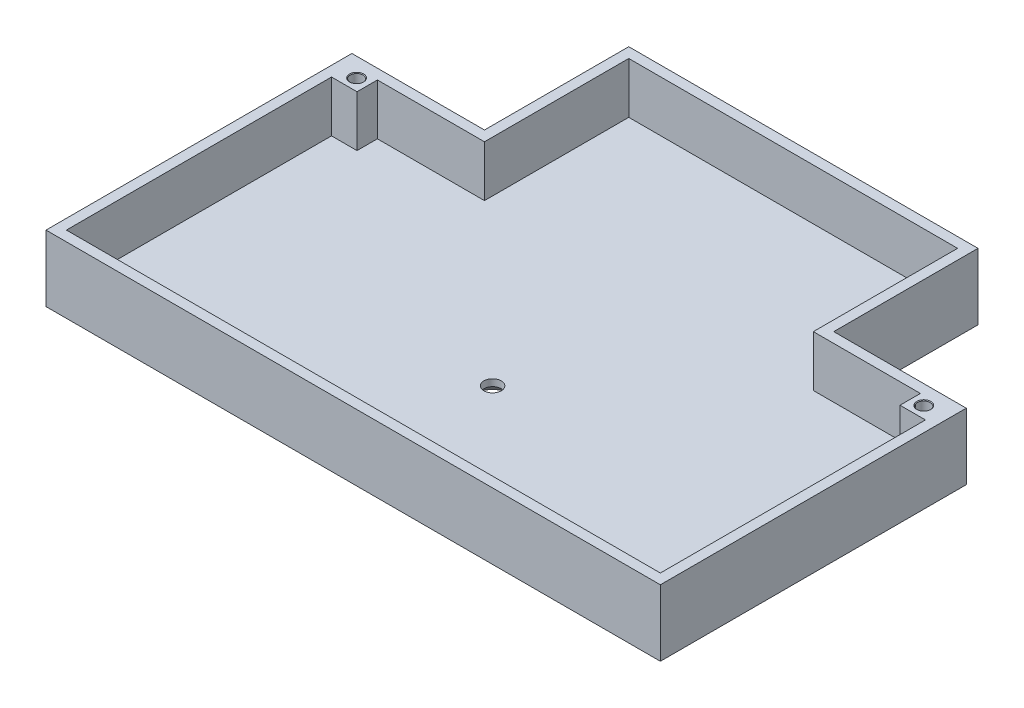
SolidWorks part; units mm, degrees
ref_plane "Front Plane" through (0, 0, 0) normal (0, 0, 1) x (1, 0, 0)
ref_plane "Top Plane" through (0, 0, 0) normal (0, 1, 0) x (1, 0, 0)
ref_plane "Right Plane" through (0, 0, 0) normal (1, 0, 0) x (0, 0, -1)
sketch "Sketch1" plane through (0, 0, 0) normal (0, 1, 0) x (1, 0, 0)
  line L1 (60.25, 30) -> (-60.25, 30)
  line L2 (60.25, 30) -> (60.25, -30)
  line L3 (60.25, -30) -> (-60.25, -30)
  line L4 (-60.25, 30) -> (-60.25, -30)
  line L5 (60.25, 30) -> (-60.25, -30) construction
  line L6 (60.25, -30) -> (-60.25, 30) construction
  point P0 (0, 0)
  dimension "D1" = 60
  dimension "D2" = 120.5
extrude "Boss-Extrude1" add sketch "Sketch1" along normal blind 3
sketch "Sketch3" plane through (0, 0, 0) normal (0, -1, 0) x (1, 0, 0)
  line L0 (-34.25, -30) -> (34.25, -30)
  line L1 (60.25, -30) -> (-60.25, -30) construction
  line L2 (34.25, -30) -> (34.25, -58.3)
  line L3 (34.25, -58.3) -> (-34.25, -58.3)
  line L4 (-34.25, -58.3) -> (-34.25, -30)
  line L5 (0, 0) -> (0, 17.3585) construction
  dimension "D1" = 26
  dimension "D2" = 28.3
extrude "Boss-Extrude3" add sketch "Sketch3" against normal blind 3
sketch "Sketch2" plane through (0, 3, 0) normal (0, 1, 0) x (1, 0, 0)
  line L0 (60.25, 30) -> (34.25, 30)
  line L2 (60.25, 30) -> (60.25, -30)
  line L3 (60.25, -30) -> (-60.25, -30)
  line L4 (-60.25, 30) -> (-60.25, -30)
  line L5 (34.25, 30) -> (34.25, 58.3)
  line L6 (34.25, 58.3) -> (-34.25, 58.3)
  line L11 (-34.25, 58.3) -> (-34.25, 30)
  line L12 (-34.25, 30) -> (-60.25, 30)
  line L13 (-32.25, 28) -> (-58.25, 28)
  line L14 (-58.25, 28) -> (-58.25, -28)
  line L15 (58.25, -28) -> (-58.25, -28)
  line L16 (58.25, 28) -> (58.25, -28)
  line L17 (58.25, 28) -> (32.25, 28)
  line L18 (32.25, 28) -> (32.25, 56.3)
  line L19 (32.25, 56.3) -> (-32.25, 56.3)
  line L20 (-32.25, 56.3) -> (-32.25, 28)
  point P0 (0, 0)
  point P7 (0, 0)
  dimension "D1" = 2
extrude "Boss-Extrude2" add sketch "Sketch2" along normal blind 10
hole_wizard "CSK for M3 Hex Socket Countersunk Cap Screw1" positions "Sketch4" profile "Sketch5" countersink size "M3" standard "ISO" end condition through all
sketch "Sketch4" plane through (0, 0, 0) normal (0, -1, 0) x (-1, 0, 0)
  line L0 (60.25, -30) -> (-60.25, -30) construction
  line L1 (0, 0) -> (0, 13.3485) construction
  point P0 (0, -2.66)
  dimension "D1" = 27.34
sketch "Sketch5" plane through (0, 0, 2.66) normal (1, 0, 0) x (0, 0, -1)
  line L0 (0, 0) -> (0, 13)
  line L1 (0, 13) -> (1.7, 13)
  line L2 (1.7, 13) -> (1.7, 1.66)
  line L3 (1.7, 1.66) -> (3.36, 0)
  line L5 (3.36, 0) -> (0, 0)
  line L6 (-1.7, 1.66) -> (-3.36, 0) construction
  line L11 (0, -6.35) -> (0, 107.95) construction
  dimension "Thru Hole Dia." = 3.4
  dimension "Thru Hole Depth" = 13
  dimension "Near C'Sink Dia." = 6.72
  dimension "Near C'Sink Angle" = 90
sketch "Sketch6" plane through (0, 3, 0) normal (0, 1, 0) x (1, 0, 0)
  line L1 (-58.25, 28) -> (-53.25, 28)
  line L2 (-58.25, 28) -> (-58.25, 24)
  line L3 (-58.25, 24) -> (-53.25, 24)
  line L4 (-53.25, 28) -> (-53.25, 24)
  dimension "D1" = 4
  dimension "D2" = 5
extrude "Boss-Extrude4" add sketch "Sketch6" along normal blind 10
hole_wizard "Ø2.5 (2.5) Diameter Hole1" positions "Sketch7" profile "Sketch8" hole size "Ø2.5" standard "ISO"
sketch "Sketch7" plane through (0, 13, 0) normal (0, 1, 0) x (1, 0, 0)
  line L7 (-32.25, 28) -> (-53.25, 28) construction
  line L8 (-58.25, 24) -> (-58.25, -28) construction
  point P0 (-55.626, 26.296)
  dimension "D1" = 1.704
  dimension "D2" = 2.624
sketch "Sketch8" plane through (-55.626, 13, -26.296) normal (1, 0, 0) x (0, 0, 1)
  line L0 (0, 0) -> (0, 8.7511)
  line L1 (0, 8.7511) -> (1.25, 8)
  line L2 (1.25, 8) -> (1.25, 0.125)
  line L3 (1.25, 0.125) -> (1.375, 0)
  line L5 (1.375, 0) -> (0, 0)
  line L6 (-1.25, 0.125) -> (-1.375, 0) construction
  line L10 (0, 8.7511) -> (-1.25, 8) construction
  line L11 (0, -6.35) -> (0, 107.95) construction
  dimension "Hole Dia." = 2.5
  dimension "Hole Depth" = 8
  dimension "Near C'Sink Dia." = 2.75
  dimension "Near C'Sink Angle" = 90
  dimension "Drill Angle" = 118
mirror "Mirror1" about plane through (0, 0, 0) normal (1, 0, 0) of "Boss-Extrude4", "Ø2.5 (2.5) Diameter Hole1"
